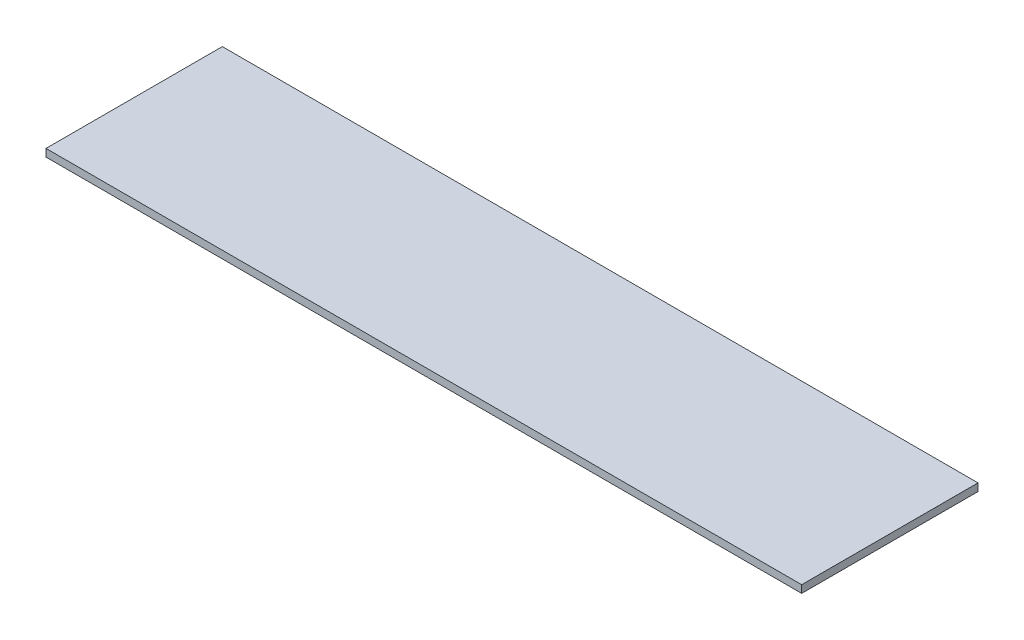
SolidWorks part; units mm, degrees
ref_plane "Front Plane" through (0, 0, 0) normal (0, 0, 1) x (1, 0, 0)
ref_plane "Top Plane" through (0, 0, 0) normal (0, 1, 0) x (1, 0, 0)
ref_plane "Right Plane" through (0, 0, 0) normal (1, 0, 0) x (0, 0, -1)
sketch "Sketch1" plane through (0, 0, 0) normal (0, 1, 0) x (1, 0, 0)
  line L1 (-1500, 350) -> (1500, 350)
  line L2 (-1500, 350) -> (-1500, -350)
  line L3 (-1500, -350) -> (1500, -350)
  line L4 (1500, 350) -> (1500, -350)
  dimension "D1" = 3000
  dimension "D2" = 700
  dimension "D3" = 350
  dimension "D4" = 1500
extrude "Boss-Extrude1" add sketch "Sketch1" along normal blind 30
